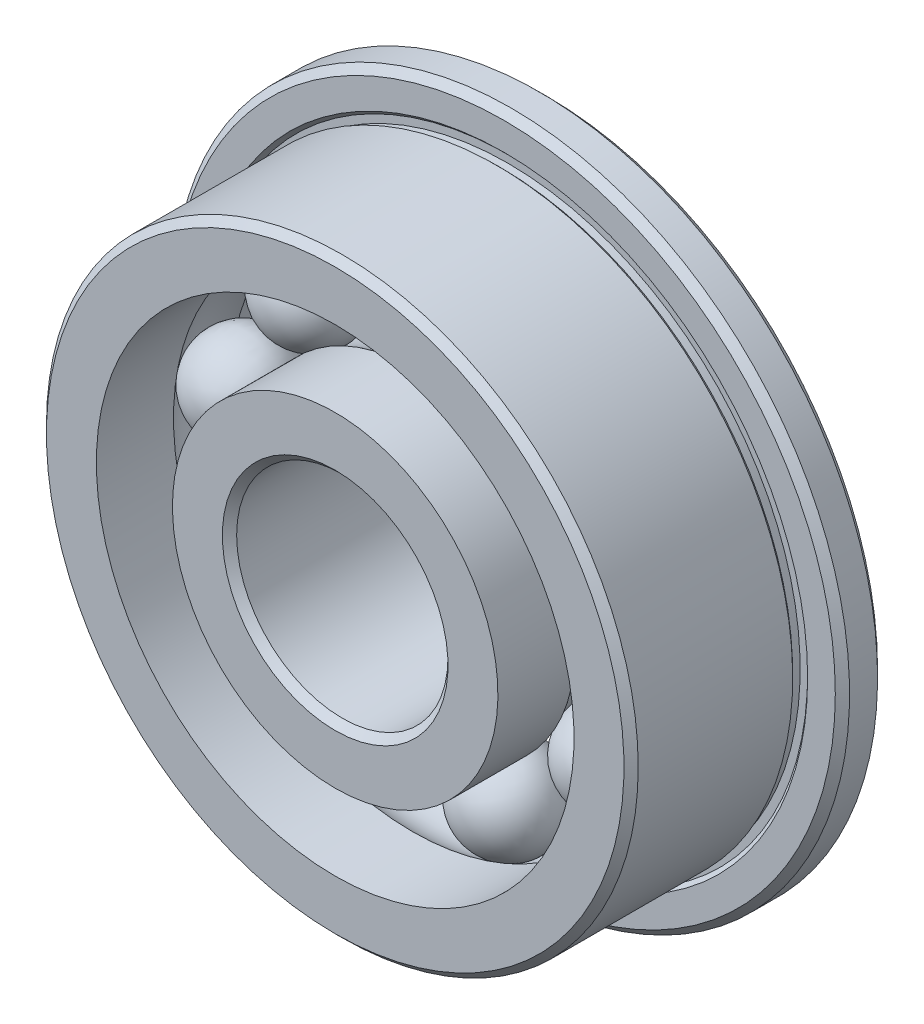
SolidWorks part; units mm, degrees
ref_plane "Front Plane" through (0, 0, 0) normal (0, 0, 1) x (1, 0, 0)
ref_plane "Top Plane" through (0, 0, 0) normal (0, 1, 0) x (1, 0, 0)
ref_plane "Right Plane" through (0, 0, 0) normal (1, 0, 0) x (0, 0, -1)
sketch "Sketch1" plane through (0, 0, 0) normal (1, 0, 0) x (0, 0, -1)
  line L0 (0, 7) -> (0, -7) construction
  line L1 (-2.5, 7) -> (2.5, 7) construction
  line L2 (0, 0) -> (2.5, 0) construction
  line L3 (2.5, 8) -> (2.5, -8) construction
  line L4 (2.5, -8) -> (1.5, -8) construction
  line L5 (2.5, 2.5) -> (0, 2.5) construction
  line L6 (2.5, 2.5) -> (2.5, -2.5) construction
  dimension "OD" = 14
  dimension "Width" = 5
  dimension "Flange Thickness" = 1
  dimension "ID" = 5
  dimension "Flange OD" = 16
sketch "Sketch2" plane through (0, 0, 0) normal (1, 0, 0) x (0, 0, -1)
  line L0 (2.5, 8) -> (1.5, 8)
  line L1 (1.5, 8) -> (1.5, 7.1768)
  line L2 (1.3232, 7) -> (-2.5, 7)
  line L3 (-2.5, 7) -> (-2.5, 5.65)
  line L4 (-2.5, 5.65) -> (-0.675, 5.65)
  line L5 (2.5, 8) -> (2.5, -8) construction
  line L6 (2.5, 5.65) -> (2.5, 8)
  line L7 (2.5, 2.5) -> (-2.5, 2.5)
  line L8 (-2.5, 2.5) -> (-2.5, 3.85)
  line L9 (-2.5, 3.85) -> (-0.675, 3.85)
  line L10 (2.5, 3.85) -> (2.5, 2.5)
  line L11 (0, 7) -> (0, 2.5) construction
  line L12 (-1.125, 4.75) -> (1.125, 4.75) construction
  line L13 (0.675, 5.65) -> (2.5, 5.65)
  line L14 (0.675, 3.85) -> (2.5, 3.85)
  line L15 (1.5, 7.1768) -> (1.5884, 7.0884)
  line L16 (1.5884, 7.0884) -> (1.5884, 6.9116)
  line L17 (1.5884, 6.9116) -> (1.4116, 6.9116)
  line L18 (1.4116, 6.9116) -> (1.3232, 7)
  line L19 (1.5, 7) -> (1.5884, 6.9116) construction
  line L20 (1.5884, 7.0884) -> (1.4116, 6.9116) construction
  line L21 (1.3232, 7) -> (1.5, 7) construction
  line L22 (1.5, 7) -> (1.5, 7.1768) construction
  circle A0 centre (0, 4.75) radius 1.125 construction
  arc A1 (-0.675, 5.65) -> (0.675, 5.65) centre (0, 4.75) cw
  arc A2 (-0.675, 3.85) -> (0.675, 3.85) centre (0, 4.75) ccw
  dimension "D1" = 4.5
  dimension "Ball Dia." = 2.25
  dimension "D2" = 135
  dimension "D3" = 0.25
  dimension "D4" = 1.8
  dimension "Race Thikness" = 1.35
revolve "Revolve1" add sketch "Sketch2" angle 360 about L2
fillet "Fillet1" radius 0.1688 3 edges at (0, -8, -2.5) (0, -8, -1.5) (0, -7, 2.5) profile chamfer
sketch "Sketch3" plane through (0, 0, 0) normal (0, 0, 1) x (1, 0, 0)
  line L0 (-2.5, 0) -> (2.5, 0) construction
  line L1 (-7, 0) -> (7, 0) construction
  point P5 (0, 0)
  dimension "ID2" = 5
  dimension "OD2" = 14
fillet "Fillet2" radius 0.1688 2 edges at (0, -2.5, -2.5) (0, -2.5, 2.5) profile chamfer
sketch "Sketch7" plane through (0, 0, 0) normal (0, 0, 1) x (1, 0, 0)
  line L0 (0, 5.875) -> (0, 3.625)
  line L1 (0, 8) -> (0, -8) construction
  line L2 (-1.4322, 5.875) -> (0, 0) construction
  line L3 (0, 0) -> (1.4322, 5.875) construction
  line L4 (1.4322, 5.875) -> (-1.4322, 5.875) construction
  circle A0 centre (0, 4.75) radius 1.125 construction
  circle A1 centre (0, 0) radius 5.875 construction
  circle A2 centre (0, 0) radius 3.625 construction
  arc A4 (0, 5.875) -> (0, 3.625) centre (0, 4.75) ccw
  dimension "D1" = 27.4
revolve "Revolve3" add sketch "Sketch7" angle 360 about L0
pattern_circular "CirPattern3" count 9 over 360 about axis through (0, 0, 0) along (0, 0, 1) of bodies 107
sketch "Sketch8" plane through (0, 0, 0) normal (1, 0, 0) x (0, 0, -1)
  line L0 (-2.5, 7) -> (2.5, 7) construction
  line L1 (2.5, 7) -> (2.5, 8) construction
  line L2 (-2.5, -7) -> (2.5, -7) construction
  line L3 (2.5, 8) -> (2.5, -8) construction
  dimension "D1" = 14
equation "\"Ball Dia.@Sketch2\" = ( \"OD@Sketch1\" - \"ID@Sketch1\" ) * .25"
equation "\"D3@Sketch2\"=\"Flange Thickness@Sketch1\"/4"
equation "\"D1@Fillet1\" = \"Race Thikness@Sketch2\" / 8"
equation "\"ID2@Sketch3\" = \"ID@Sketch1\""
equation "\"OD2@Sketch3\" = \"OD@Sketch1\""
equation "\"D1@Fillet2\" = \"Race Thikness@Sketch2\" / 8"
equation "\"D1@CirPattern3\"=360/\"D1@Sketch7\"-4"
equation "\"D4@Sketch2\" = ( \"OD@Sketch1\" - \"ID@Sketch1\" ) * .2"
